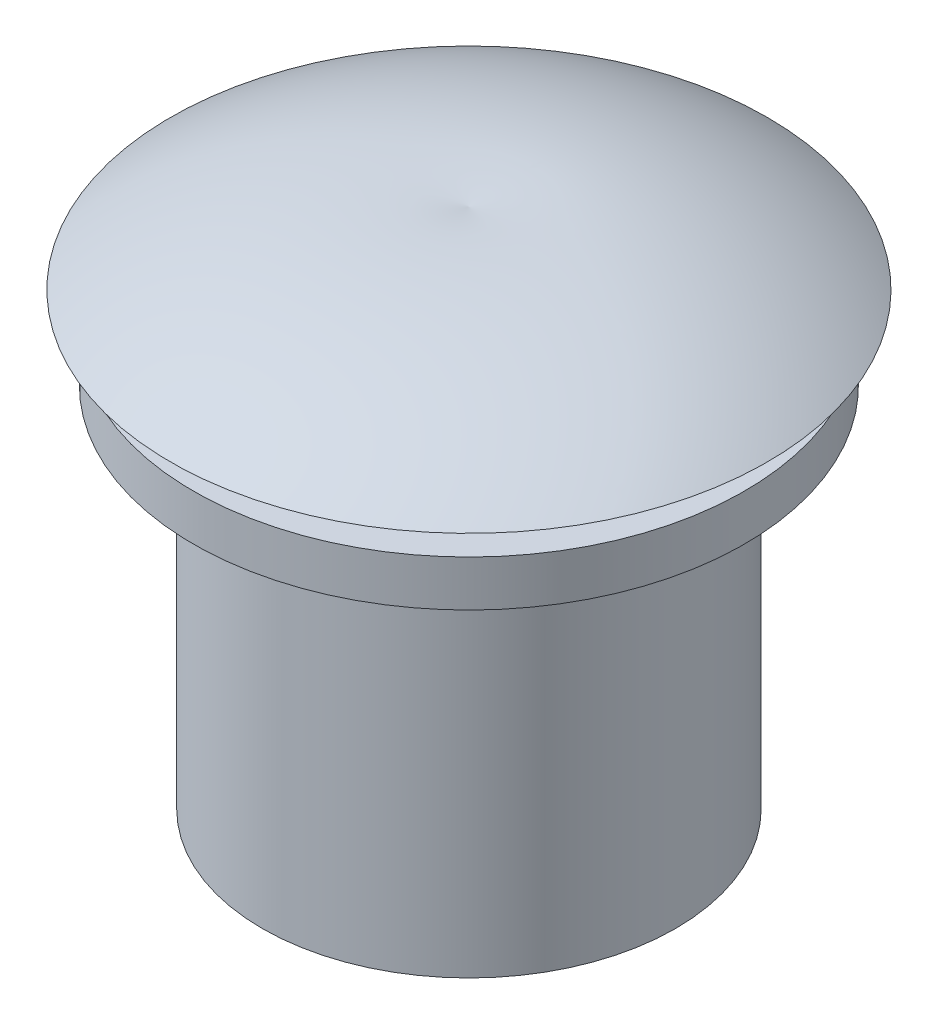
SolidWorks part; units mm, degrees
ref_plane "Front Plane" through (0, 0, 0) normal (0, 0, 1) x (1, 0, 0)
ref_plane "Top Plane" through (0, 0, 0) normal (0, 1, 0) x (1, 0, 0)
ref_plane "Right Plane" through (0, 0, 0) normal (1, 0, 0) x (0, 0, -1)
sketch "Sketch1" plane through (0, 0, 0) normal (0, 0, 1) x (1, 0, 0)
  line L0 (0, 0) -> (0.2223, 0)
  line L1 (0.5715, 0) -> (0.5715, 1.016)
  line L2 (0.5715, 1.016) -> (0.762, 1.016)
  line L3 (0.762, 1.016) -> (0.762, 1.143)
  line L4 (0.762, 1.143) -> (0.508, 1.143)
  line L5 (0.508, 1.143) -> (0.508, 1.2446)
  line L6 (0, 0) -> (0, 1.4435)
  line L7 (0.508, 1.2446) -> (0.8255, 1.2446)
  line L8 (0.3492, 0) -> (0.5715, 0)
  line L10 (0.2223, 0) -> (0.2223, 0.8001)
  line L11 (0.2223, 0.8001) -> (0.3492, 0.8001)
  line L12 (0.3492, 0) -> (0.3492, 0.8001)
  arc A1 (0, 1.4435) -> (0.8255, 1.2446) centre (0.1501, 0.254) cw
  point P16 (0.2858, 0.8001)
  dimension "D1" = 0.5715
  dimension "D2" = 1.016
  dimension "D3" = 0.1905
  dimension "D4" = 0.127
  dimension "D5" = 0.254
  dimension "D6" = 0.1016
  dimension "D7" = 0.3175
  dimension "D8" = 0.127
  dimension "D9" = 0.8001
revolve "Revolve1" add sketch "Sketch1" angle 360 about L6
